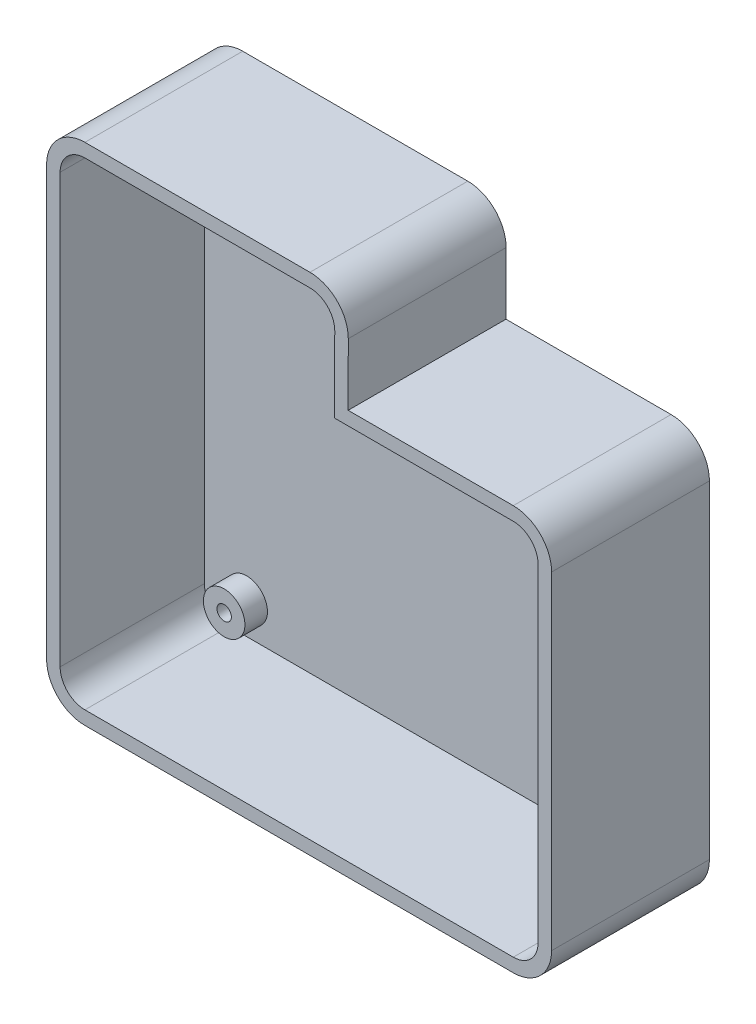
SolidWorks part; units mm, degrees
ref_plane "Front Plane" through (0, 0, 0) normal (0, 0, 1) x (1, 0, 0)
ref_plane "Top Plane" through (0, 0, 0) normal (0, 1, 0) x (1, 0, 0)
ref_plane "Right Plane" through (0, 0, 0) normal (1, 0, 0) x (0, 0, -1)
sketch "Sketch1" plane through (0, 0, 0) normal (0, 0, 1) x (1, 0, 0)
  line L30 (41.4796, 169.7032) -> (-8.4304, 169.7032)
  line L31 (-16.9304, 161.2032) -> (-16.9304, 66.2032)
  line L32 (-8.4304, 57.7032) -> (86.5696, 57.7032)
  line L33 (95.0696, 66.2032) -> (95.0696, 138.9232)
  line L34 (86.5696, 147.4232) -> (84.5796, 147.4232)
  line L35 (84.5796, 147.4232) -> (78.2296, 147.4232)
  line L36 (78.2296, 147.4232) -> (56.6396, 147.4232)
  line L37 (56.6396, 147.4232) -> (50.2896, 147.4232)
  line L38 (50.2896, 147.4232) -> (49.9476, 147.4232)
  line L39 (49.9476, 147.4232) -> (49.9796, 161.2032)
  circle A0 centre (-1.5835, 154.761) radius 1.6
  circle A1 centre (38.1086, 155.5526) radius 1.6
  circle A2 centre (-4.5498, 67.7845) radius 1.6
  circle A3 centre (76.818, 70.2075) radius 1.6
  arc A17 (-8.4304, 169.7032) -> (-16.9304, 161.2032) centre (-8.4304, 161.2032) ccw
  arc A18 (-16.9304, 66.2032) -> (-8.4304, 57.7032) centre (-8.4304, 66.2032) ccw
  arc A19 (86.5696, 57.7032) -> (95.0696, 66.2032) centre (86.5696, 66.2032) ccw
  arc A20 (95.0696, 138.9232) -> (86.5696, 147.4232) centre (86.5696, 138.9232) ccw
  arc A21 (49.9796, 161.2032) -> (41.4796, 169.7032) centre (41.4796, 161.2032) ccw
extrude "Boss-Extrude1" add sketch "Sketch1" along normal blind 35
sketch "Sketch4" plane through (0, 0, 35) normal (0, 0, 1) x (1, 0, 0)
  line L18 (41.4796, 164.7032) -> (-8.4304, 164.7032)
  line L19 (-11.9304, 161.2032) -> (-11.9304, 66.2032)
  line L20 (-8.4304, 62.7032) -> (86.5696, 62.7032)
  line L21 (90.0696, 66.2032) -> (90.0696, 138.9232)
  line L22 (86.5696, 142.4232) -> (44.936, 142.4232)
  line L23 (44.936, 142.4232) -> (44.9796, 161.2077)
  line L24 (41.4796, 164.7032) -> (-8.4304, 164.7032)
  line L25 (-11.9304, 161.2032) -> (-11.9304, 66.2032)
  line L26 (-8.4304, 62.7032) -> (86.5696, 62.7032)
  line L27 (90.0696, 66.2032) -> (90.0696, 138.9232)
  line L28 (86.5696, 142.4232) -> (44.936, 142.4232)
  line L29 (44.936, 142.4232) -> (44.9796, 161.2077)
  arc A15 (44.9796, 161.2077) -> (41.4796, 164.7032) centre (41.4796, 161.2032) ccw
  arc A16 (-8.4304, 164.7032) -> (-11.9304, 161.2032) centre (-8.4304, 161.2032) ccw
  arc A17 (-11.9304, 66.2032) -> (-8.4304, 62.7032) centre (-8.4304, 66.2032) ccw
  arc A18 (86.5696, 62.7032) -> (90.0696, 66.2032) centre (86.5696, 66.2032) ccw
  arc A19 (90.0696, 138.9232) -> (86.5696, 142.4232) centre (86.5696, 138.9232) ccw
  arc A20 (44.9796, 161.2077) -> (41.4796, 164.7032) centre (41.4796, 161.2032) ccw
  arc A21 (-8.4304, 164.7032) -> (-11.9304, 161.2032) centre (-8.4304, 161.2032) ccw
  arc A22 (-11.9304, 66.2032) -> (-8.4304, 62.7032) centre (-8.4304, 66.2032) ccw
  arc A23 (86.5696, 62.7032) -> (90.0696, 66.2032) centre (86.5696, 66.2032) ccw
  arc A24 (90.0696, 138.9232) -> (86.5696, 142.4232) centre (86.5696, 138.9232) ccw
  dimension "D1" = 5
shell "Shell3" thickness 3
extrude "Cut-Extrude2" cut sketch "Sketch4" against normal offset from surface (27 mm away) 5 up to face at (40.8268, 121.6852, 3)
